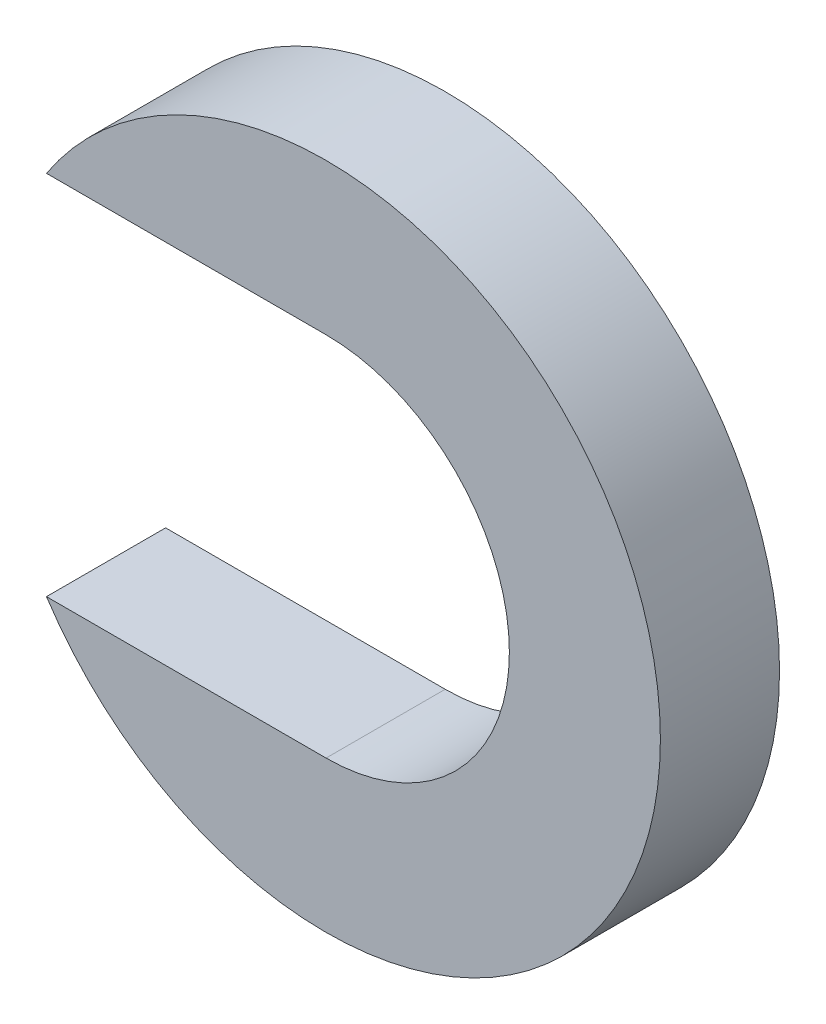
SolidWorks part; units mm, degrees
ref_plane "Alzado" through (0, 0, 0) normal (0, 0, 1) x (1, 0, 0)
ref_plane "Planta" through (0, 0, 0) normal (0, 1, 0) x (1, 0, 0)
ref_plane "Vista lateral" through (0, 0, 0) normal (1, 0, 0) x (0, 0, -1)
sketch "Croquis1" plane through (0, 0, 0) normal (0, 0, 1) x (1, 0, 0)
  line L0 (-13.9822, 0) -> (0, 0) construction
  line L1 (-13.9822, 5) -> (0, 5)
  line L2 (-13.9822, -5) -> (0, -5)
  arc A0 (-7.6272, -5) -> (-7.6272, 5) centre (0, 0) ccw
  arc A1 (-13.9822, 5) -> (-13.9822, -5) centre (-13.9822, 0) ccw
  arc A2 (0, -5) -> (0, 5) centre (0, 0) ccw
  point P4 (-6.9911, 0)
  dimension "D1" = 18.24
  dimension "D2" = 5
  dimension "D3" = 13.9822
extrude "Saliente-Extruir1" add sketch "Croquis1" along normal blind 3.25 contours A2 L2 A0 L1
